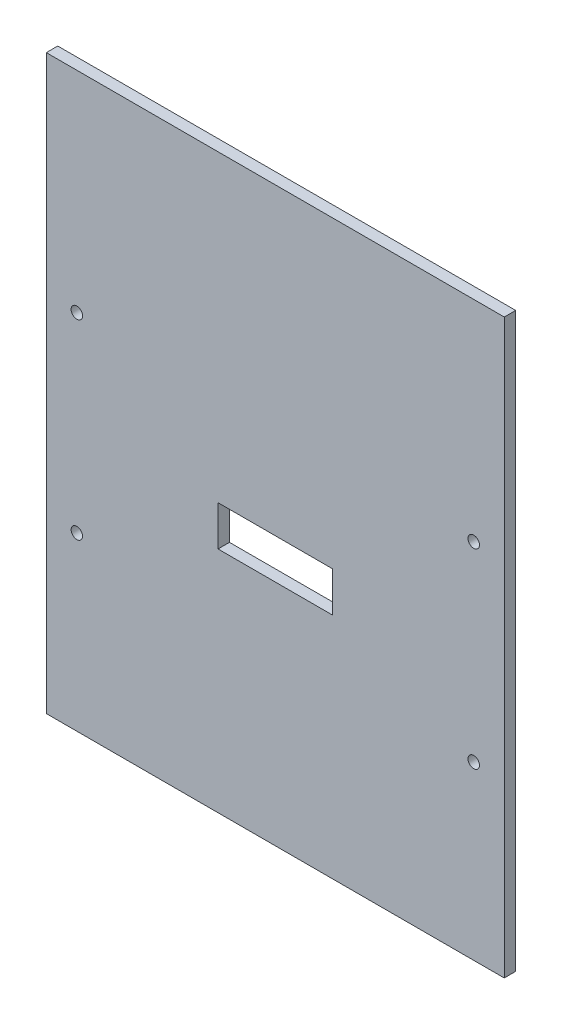
SolidWorks part; units mm, degrees
ref_plane "Front Plane" through (0, 0, 0) normal (0, 0, 1) x (1, 0, 0)
ref_plane "Top Plane" through (0, 0, 0) normal (0, 1, 0) x (1, 0, 0)
ref_plane "Right Plane" through (0, 0, 0) normal (1, 0, 0) x (0, 0, -1)
sketch "Sketch1" plane through (0, 0, 0) normal (0, 0, 1) x (1, 0, 0)
  line L0 (60, 150) -> (60, 95) construction
  line L1 (0, 0) -> (120, 0)
  line L2 (0, 0) -> (0, 150)
  line L3 (0, 150) -> (120, 150)
  line L4 (120, 0) -> (120, 150)
  line L7 (60, 95) -> (60, 0) construction
  circle A0 centre (112, 95) radius 1.5
  circle A1 centre (112, 45) radius 1.5
  circle A2 centre (8, 45) radius 1.5
  circle A3 centre (8, 95) radius 1.5
extrude "Boss-Extrude1" add sketch "Sketch1" along normal blind 3
sketch "Sketch2" plane through (0, 0, 0) normal (0, 0, -1) x (-1, 0, 0)
  circle A4 centre (-42.75, 53.3041) radius 1.25
  circle A5 centre (-42.75, 53.3041) radius 2.4034
  circle A6 centre (-47.6, 16.1541) radius 2.3977
  circle A7 centre (-47.6, 16.1541) radius 1.25
  circle A8 centre (-72.4, 16.1541) radius 2.3977
  circle A9 centre (-72.4, 16.1541) radius 1.25
  circle A10 centre (-77.25, 53.3041) radius 2.4034
  circle A11 centre (-77.25, 53.3041) radius 1.25
extrude "Boss-Extrude2" add sketch "Sketch2" along normal blind 4
sketch "Sketch3" plane through (0, 0, 0) normal (0, 0, -1) x (-1, 0, 0)
  line L0 (-60, 150) -> (-60, 0) construction
  line L1 (-120, 150) -> (0, 150) construction
  line L2 (0, 0) -> (-120, 0) construction
  line L3 (-60, 59.861) -> (-75, 59.861) construction
  line L4 (-60, 59.861) -> (-45, 59.861) construction
  line L5 (-45, 59.861) -> (-75, 59.861)
  line L6 (-75, 59.861) -> (-75, 70.361)
  line L7 (-75, 70.361) -> (-45, 70.361)
  line L8 (-45, 70.361) -> (-45, 59.861)
extrude "Cut-Extrude1" cut sketch "Sketch3" against normal blind 10
